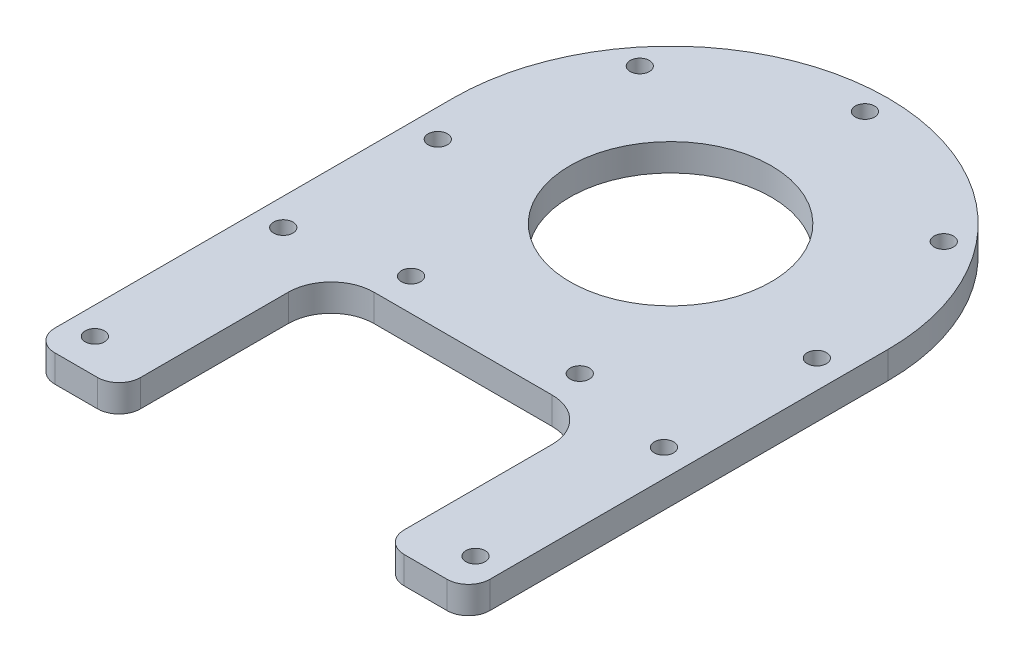
SolidWorks part; units mm, degrees
material "6061 Alloy"
ref_plane "Front Plane" through (0, 0, 0) normal (0, 0, 1) x (1, 0, 0)
ref_plane "Top Plane" through (0, 0, 0) normal (0, 1, 0) x (1, 0, 0)
ref_plane "Right Plane" through (0, 0, 0) normal (1, 0, 0) x (0, 0, -1)
sketch "Sketch1" plane through (0, 0, 0) normal (0, 1, 0) x (1, 0, 0)
  line L0 (-50.8, 24.3982) -> (-50.8, -73.6018)
  line L1 (-50.8, -73.6018) -> (50.8, -73.6018)
  line L2 (50.8, -73.6018) -> (50.8, 24.3982)
  line L3 (0, -73.6018) -> (0, 24.3982)
  line L4 (0, -81.84) -> (0, 81.84) construction
  line L5 (-50.8, 24.3982) -> (50.8, 24.3982)
  line L6 (-30.8, -73.6018) -> (-30.8, -24.0718)
  line L7 (-30.8, -24.0718) -> (30.8, -24.0718)
  line L8 (30.8, -24.0718) -> (30.8, -73.6018)
  circle A0 centre (0, 24.3982) radius 50.8
  dimension "D1" = 101.6
  dimension "D2" = 98
  dimension "D3" = 49.53
  dimension "D4" = 20
  dimension "D5" = 20
extrude "Boss-Extrude1" add sketch "Sketch1" along normal blind 6.35 contours A0 L0 L1 L6 L7 | L5 A0 L7 L3 | L5 A0 | L7 A0 L5 L3 | A0 L7 L8 L1 L2
fillet "Fillet1" radius 10 2 edges at (30.8, 3.175, 24.0718) (-30.8, 3.175, 24.0718)
sketch "Sketch3" plane through (0, 0, 0) normal (0, -1, 0) x (1, 0, 0)
  line L0 (-50.8, 73.6018) -> (-44.45, 73.6018)
  line L1 (-50.8, 73.6018) -> (-30.8, 73.6018) construction
  line L2 (-44.45, 73.6018) -> (-44.45, 65.6018)
  line L3 (50.8, 73.6018) -> (44.45, 73.6018)
  line L4 (30.8, 73.6018) -> (50.8, 73.6018) construction
  line L5 (44.45, 73.6018) -> (44.45, 65.6018)
  line L6 (-50.8, 73.6018) -> (-50.8, 13.6018)
  line L7 (-50.8, -24.3982) -> (-50.8, 73.6018) construction
  line L8 (50.8, 73.6018) -> (50.8, 13.6018)
  line L9 (50.8, 73.6018) -> (50.8, -24.3982) construction
  line L10 (-50.8, 13.6018) -> (-44.45, 13.6018)
  line L11 (-44.45, 13.6018) -> (-44.45, 21.6018)
  line L12 (50.8, 13.6018) -> (44.45, 13.6018)
  line L13 (44.45, 13.6018) -> (44.45, 21.6018)
  line L14 (50.8, -24.3982) -> (0, -24.3982)
  line L15 (0, -64.3982) -> (0, -75.1982)
  line L17 (-31.2733, -49.3378) -> (-39.717, -56.0715)
  line L18 (-38.9971, -15.4974) -> (-49.5263, -13.0941)
  line L19 (-17.3553, 11.6405) -> (-22.0413, 21.371)
  line L20 (17.3553, 11.6405) -> (22.0413, 21.371)
  line L21 (38.9971, -15.4974) -> (49.5263, -13.0941)
  line L22 (31.2733, -49.3378) -> (39.717, -56.0715)
  circle A1 centre (0, -24.3982) radius 40
  arc A2 (-50.8, -24.3982) -> (50.8, -24.3982) centre (0, -24.3982) ccw construction
  point P6 (-44.45, 65.6018)
  point P12 (44.45, 65.6018)
  point P20 (-44.45, 21.6018)
  point P22 (44.45, 21.6018)
  point P55 (19.6983, 16.5058)
  point P57 (-19.6983, 16.5058)
  point P59 (-44.2617, -14.2958)
  point P61 (-35.4951, -52.7046)
  point P63 (0, -69.7982)
  point P65 (35.4951, -52.7046)
  point P67 (44.2617, -14.2958)
  dimension "D4" = 80
  dimension "D1" = 6.35
  dimension "D2" = 8
  dimension "D3" = 60
  dimension "D5" = 7
hole_wizard "CSK for M4 Flat Head Machine Screw1" positions "Sketch3" profile "Sketch4" countersink size "M4" standard "ANSI Metric"
sketch "Sketch4" plane through (44.2617, 0, -14.2958) normal (1, 0, 0) x (0, 0, -1)
  line L0 (0, 0) -> (0, 42.5019)
  line L1 (0, 42.5019) -> (2.25, 41.15)
  line L2 (2.25, 41.15) -> (2.25, 2.45)
  line L3 (2.25, 2.45) -> (4.7, 0)
  line L5 (4.7, 0) -> (0, 0)
  line L6 (-2.25, 2.45) -> (-4.7, 0) construction
  line L10 (0, 42.5019) -> (-2.25, 41.15) construction
  line L11 (0, -6.35) -> (0, 107.95) construction
  dimension "Hole Dia." = 4.5
  dimension "Hole Depth" = 41.15
  dimension "Near C'Sink Dia." = 9.4
  dimension "Near C'Sink Angle" = 90
  dimension "Drill Angle" = 118
sketch "Sketch5" plane through (0, 0, 0) normal (0, -1, 0) x (1, 0, 0)
  circle A0 centre (0, -24.3982) radius 23.5
  dimension "D1" = 47
extrude "Cut-Extrude1" cut sketch "Sketch5" against normal through all contours A0
fillet "Fillet2" radius 5 4 edges at (30.8, 3.175, 73.6018) (50.8, 3.175, 73.6018) (-30.8, 3.175, 73.6018) (-50.8, 3.175, 73.6018)
